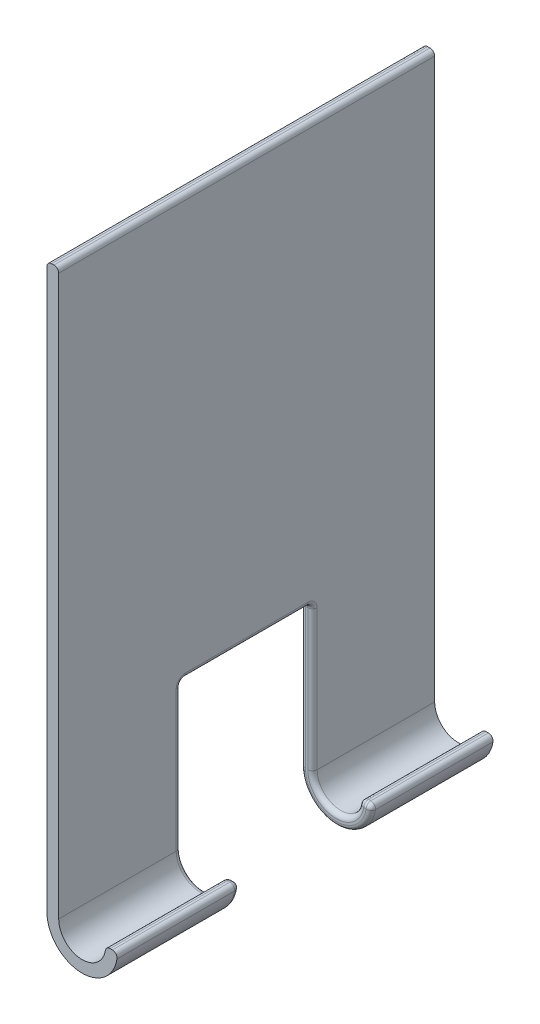
SolidWorks part; units mm, degrees
ref_plane "前视基准面" through (0, 0, 0) normal (0, 0, 1) x (1, 0, 0)
ref_plane "上视基准面" through (0, 0, 0) normal (0, 1, 0) x (1, 0, 0)
ref_plane "右视基准面" through (0, 0, 0) normal (1, 0, 0) x (0, 0, -1)
other "Configuration Table"
sketch "草图1" plane through (0, 0, 0) normal (0, 0, 1) x (1, 0, 0)
  line L0 (0, 0) -> (0, 120)
  line L1 (0, 120) -> (2.5, 120)
  line L2 (2.5, 120) -> (2.5, 0)
  line L4 (15, 0) -> (12.5, 0)
  line L5 (7.5, 0) -> (0, 0) construction
  arc A0 (2.5, 0) -> (12.5, 0) centre (7.5, 0) ccw
  arc A1 (0, 0) -> (15, 0) centre (7.5, 0) ccw
  dimension "D3" = 5
  dimension "D4" = 7.5
  dimension "D1" = 2.5
  dimension "D2" = 120
extrude "凸台-拉伸1" add sketch "草图1" along normal blind 80
sketch "草图2" plane through (2.5, 0, 0) normal (1, 0, 0) x (0, 0, -1)
  line L0 (-80, -7.5) -> (0, -7.5) construction
  line L1 (-54, 30.8611) -> (-26, 30.8611)
  line L2 (-54, 30.8611) -> (-54, -45.8611)
  line L3 (-54, -45.8611) -> (-26, -45.8611)
  line L4 (-26, 30.8611) -> (-26, -45.8611)
  line L5 (-54, 30.8611) -> (-26, -45.8611) construction
  line L6 (-54, -45.8611) -> (-26, 30.8611) construction
  point P0 (-40, -7.5)
  dimension "D1" = 28
extrude "切除-拉伸2" cut sketch "草图2" against normal mid plane 80
fillet "圆角1" radius 1 4 edges at (12.5, 0, 13) (15, 0, 13) (12.5, 0, 67) (15, 0, 67)
fillet "圆角2" radius 1 2 edges at (0, 120, 40) (2.5, 120, 40)
fillet "圆角3" radius 1 18 edges at (13.6693, 0, 26) (13.6693, 0, 54) (12.7706, -0.2362, 54) (12.7706, -0.2362, 26) (14.6822, -0.3496, 26) (14.6822, -0.3496, 54) (7.0819, -4.9825, 54) (7.0819, -4.9825, 26) (6.9214, -7.4776, 26) (6.9214, -7.4776, 54) (2.5, 15.4306, 54) (2.5, 15.4306, 26) (0, 15.4306, 26) (0, 15.4306, 54) (2.5, 30.8611, 40) (1.25, 30.8611, 26) (0, 30.8611, 40) (1.25, 30.8611, 54)
sketch "草图4" plane through (0, 0, 0) normal (-1, 0, 0) x (0, 0, 1)
  line L0 (40, 31.8611) -> (40, 119) construction
  line L1 (27, 31.8611) -> (53, 31.8611) construction
  line L2 (80, 119) -> (0, 119) construction
  line L4 (31.07, 60.3611) -> (48.93, 60.3611)
  line L5 (31.07, 60.3611) -> (31.07, 69.3611)
  line L6 (31.07, 69.3611) -> (48.93, 69.3611)
  line L7 (48.93, 60.3611) -> (48.93, 69.3611)
  line L8 (31.07, 60.3611) -> (48.93, 69.3611) construction
  line L9 (31.07, 69.3611) -> (48.93, 60.3611) construction
  point P6 (40, 64.8611)
  dimension "D1" = 17.86
  dimension "D2" = 9
  dimension "D3" = 33
extrude "凸台-拉伸2" add sketch "草图4" along normal blind 10
sketch "草图5" plane through (0, 0, 48.93) normal (0, 0, 1) x (1, 0, 0)
  line L0 (-10, 60.3611) -> (-10, 69.3611) construction
  line L5 (0, 60.3611) -> (0, 69.3611)
  line L6 (0, 69.3611) -> (-10, 69.3611)
  line L7 (-10, 69.3611) -> (-10, 60.3611)
  line L8 (-10, 60.3611) -> (0, 60.3611)
  line L11 (-10, 69.3611) -> (-10, 60.3611)
  arc A0 (-10, 69.3611) -> (-10, 60.3611) centre (-10, 64.8611) ccw
  dimension "D1" = 0
extrude "凸台-拉伸3" add sketch "草图5" against normal blind 17.89
sketch "草图6" plane through (0, 0, 48.93) normal (0, 0, 1) x (1, 0, 0)
  circle A0 centre (-10, 64.8611) radius 2
  dimension "D1" = 4
extrude "切除-拉伸3" cut sketch "草图6" against normal through all
